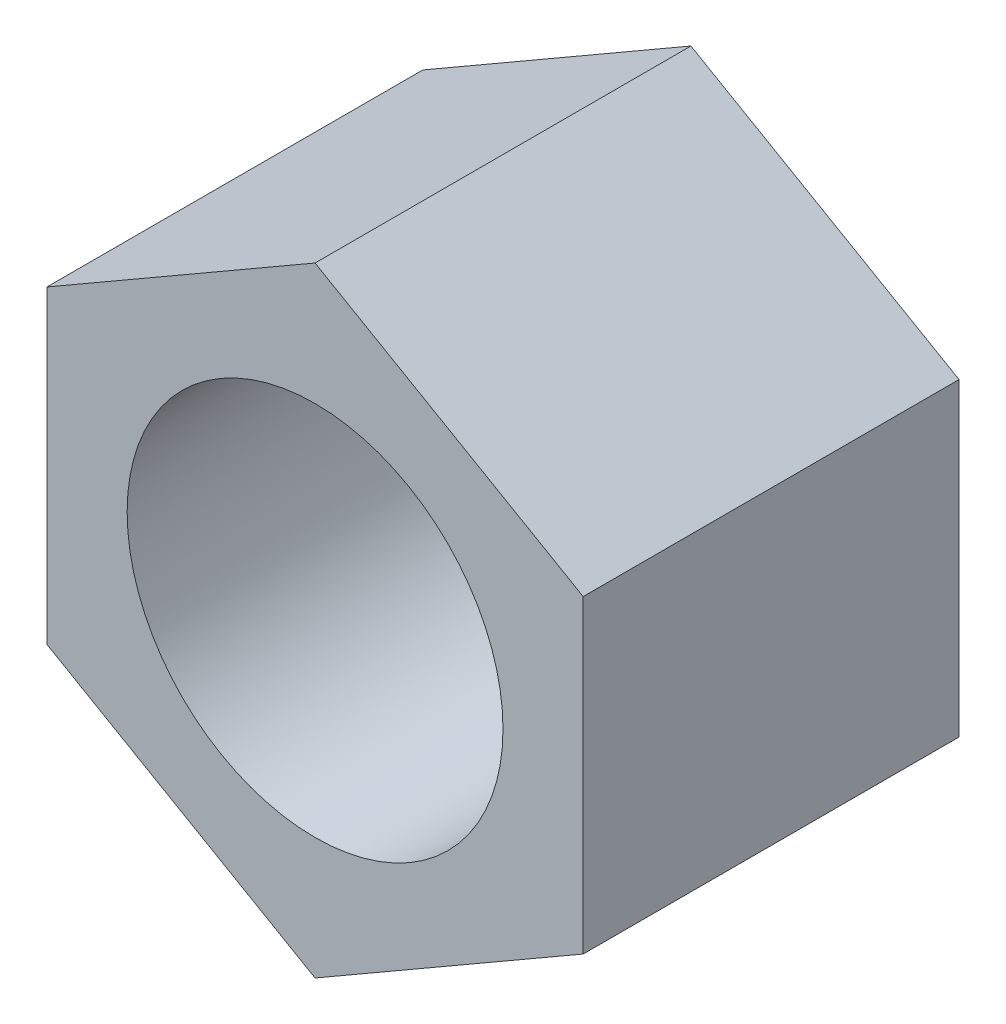
SolidWorks part; units mm, degrees
ref_plane "前视基准面" through (0, 0, 0) normal (0, 0, 1) x (1, 0, 0)
ref_plane "上视基准面" through (0, 0, 0) normal (0, 1, 0) x (1, 0, 0)
ref_plane "右视基准面" through (0, 0, 0) normal (1, 0, 0) x (0, 0, -1)
sketch "草图1" plane through (0, 0, 0) normal (0, 0, 1) x (1, 0, 0)
  line L1 (0, -4.9421) -> (4.28, -2.4711)
  line L2 (4.28, -2.4711) -> (4.28, 2.4711)
  line L3 (4.28, 2.4711) -> (0, 4.9421)
  line L4 (0, 4.9421) -> (-4.28, 2.4711)
  line L5 (-4.28, 2.4711) -> (-4.28, -2.4711)
  line L6 (-4.28, -2.4711) -> (0, -4.9421)
  circle A0 centre (0, 0) radius 3
  circle A1 centre (0, 0) radius 4.28 construction
extrude "凸台-拉伸1" add sketch "草图1" along normal blind 6
